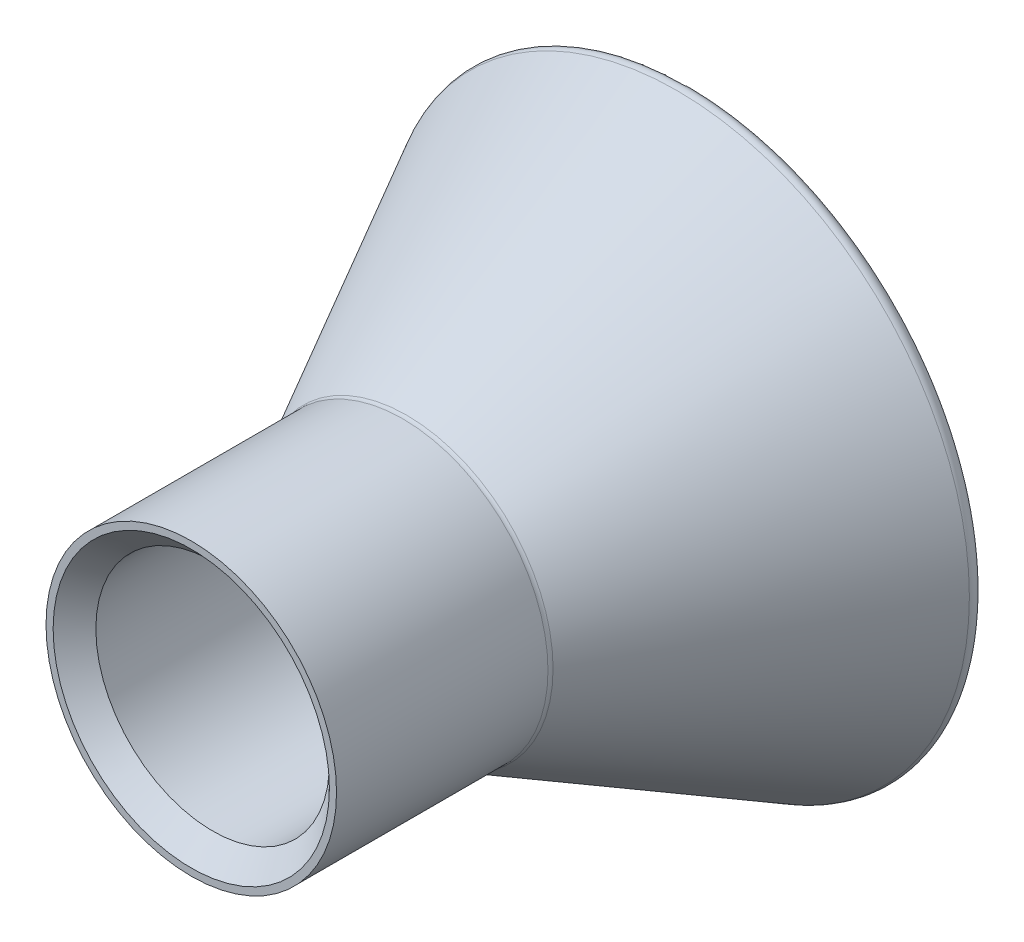
SolidWorks part; units mm, degrees
ref_plane "Front Plane" through (0, 0, 0) normal (0, 0, 1) x (1, 0, 0)
ref_plane "Top Plane" through (0, 0, 0) normal (0, 1, 0) x (1, 0, 0)
ref_plane "Right Plane" through (0, 0, 0) normal (1, 0, 0) x (0, 0, -1)
sketch "Sketch2" plane through (0, 0, 0) normal (1, 0, 0) x (0, 0, -1)
  line L0 (-15, 0) -> (0, 0)
  line L1 (0, 0) -> (0, 10.2)
  line L2 (0, 10.2) -> (-15, 10.2)
  line L3 (-15, 10.2) -> (-15, 0)
  line L4 (0, 10.2) -> (20, 21)
  line L5 (20, 21) -> (20, 19)
  line L6 (20, 19) -> (0, 8.2)
  point P2 (-100.573, 114.4408)
  dimension "D1" = 10.2
  dimension "D2" = 2
  dimension "D3" = 15
  dimension "D4" = 20
  dimension "D5" = 19
  dimension "D6" = 2
revolve "Revolve1" add sketch "Sketch2" angle 360 about L0
sketch "Sketch3" plane through (0, 0, 15) normal (0, 0, 1) x (1, 0, 0)
  circle A0 centre (0, 0) radius 8.2
  dimension "D1" = 16.4
extrude "Cut-Extrude1" cut sketch "Sketch3" against normal blind 40
chamfer "Chamfer1" distance 1.5 angle 45 1 edges at (8.2, 0, 15)
fillet "Fillet2" radius 0.6 2 edges at (21, 0, -20) (19, 0, -20)
fillet "Fillet3" radius 0.6 1 edges at (10.2, 0, 0)
fillet "Fillet4" radius 0.6 1 edges at (8.2, 0, 0)
